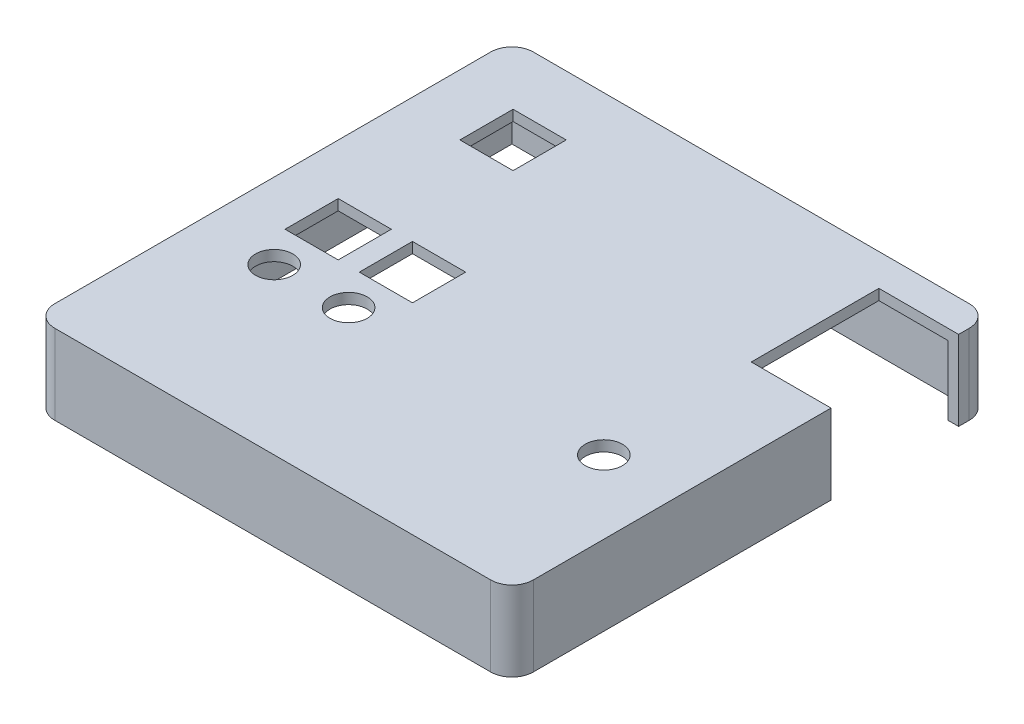
SolidWorks part; units mm, degrees
ref_plane "Front Plane" through (0, 0, 0) normal (0, 0, 1) x (1, 0, 0)
ref_plane "Top Plane" through (0, 0, 0) normal (0, 1, 0) x (1, 0, 0)
ref_plane "Right Plane" through (0, 0, 0) normal (1, 0, 0) x (0, 0, -1)
sketch "Sketch1" plane through (0, 0, 0) normal (0, 1, 0) x (1, 0, 0)
  line L1 (0, 0) -> (90, 0)
  line L2 (0, 0) -> (0, 90)
  line L3 (0, 90) -> (90, 90)
  line L4 (90, 0) -> (90, 90)
  dimension "D1" = 90
  dimension "D2" = 90
extrude "Boss-Extrude1" add sketch "Sketch1" against normal blind 15
sketch "Sketch2" plane through (90, 0, 0) normal (1, 0, 0) x (0, 0, -1)
  line L0 (0, 0) -> (90, 0) construction
  line L1 (60, 0) -> (84, 0)
  line L2 (60, 0) -> (60, -15)
  line L3 (60, -15) -> (84, -15)
  line L4 (84, 0) -> (84, -15)
  line L5 (0, -15) -> (90, -15) construction
  line L6 (90, -15) -> (90, 0) construction
  dimension "D1" = 6
  dimension "D2" = 30
extrude "Cut-Extrude1" cut sketch "Sketch2" against normal blind 15
shell "Shell1" thickness 2
sketch "Sketch3" plane through (0, 0, 0) normal (0, 1, 0) x (1, 0, 0)
  line L0 (0, 0) -> (90, 0) construction
  line L1 (0, 90) -> (0, 0) construction
  line L2 (90, 0) -> (90, 60) construction
  circle A0 centre (14.27, 31) radius 3.5
  circle A1 centre (28.27, 31) radius 3.5
  circle A2 centre (76.27, 31) radius 3.5
  dimension "D1" = 7
  dimension "D2" = 7
  dimension "D3" = 7
  dimension "D4" = 31
  dimension "D5" = 31
  dimension "D6" = 31
  dimension "D7" = 14.27
  dimension "D8" = 28.27
  dimension "D9" = 13.73
extrude "Cut-Extrude2" cut sketch "Sketch3" against normal blind 4
sketch "Sketch4" plane through (0, 0, 0) normal (0, 1, 0) x (1, 0, 0)
  line L0 (0, 90) -> (0, 0) construction
  line L17 (9.53, 37.78) -> (19.53, 37.78)
  line L18 (9.53, 37.78) -> (9.53, 47.78)
  line L19 (9.53, 47.78) -> (19.53, 47.78)
  line L20 (19.53, 37.78) -> (19.53, 47.78)
  line L21 (9.53, 37.78) -> (19.53, 47.78) construction
  line L22 (9.53, 47.78) -> (19.53, 37.78) construction
  line L23 (23.5, 37.78) -> (33.5, 37.78)
  line L24 (23.5, 37.78) -> (23.5, 47.78)
  line L25 (23.5, 47.78) -> (33.5, 47.78)
  line L26 (33.5, 37.78) -> (33.5, 47.78)
  line L27 (23.5, 37.78) -> (33.5, 47.78) construction
  line L28 (23.5, 47.78) -> (33.5, 37.78) construction
  line L29 (11.43, 68.77) -> (21.43, 68.77)
  line L30 (11.43, 68.77) -> (11.43, 78.77)
  line L31 (11.43, 78.77) -> (21.43, 78.77)
  line L32 (21.43, 68.77) -> (21.43, 78.77)
  line L33 (11.43, 68.77) -> (21.43, 78.77) construction
  line L34 (11.43, 78.77) -> (21.43, 68.77) construction
  line L35 (0, 0) -> (90, 0) construction
  line L36 (90, 90) -> (0, 90) construction
  point P0 (14.53, 42.78)
  point P5 (28.5, 42.78)
  point P10 (16.43, 73.77)
  point P15 (14.53, 37.78)
  dimension "D1" = 10
  dimension "D2" = 10
  dimension "D3" = 10
  dimension "D4" = 10
  dimension "D5" = 10
  dimension "D6" = 10
  dimension "D7" = 14.53
  dimension "D8" = 28.5
  dimension "D9" = 42.78
  dimension "D10" = 42.78
  dimension "D11" = 16.43
  dimension "D12" = 16.23
extrude "Cut-Extrude3" cut sketch "Sketch4" against normal blind 4
fillet "Fillet1" radius 4 4 edges at (0, -7.5, -90) (0, -7.5, 0) (90, -7.5, -90) (90, -7.5, 0)
